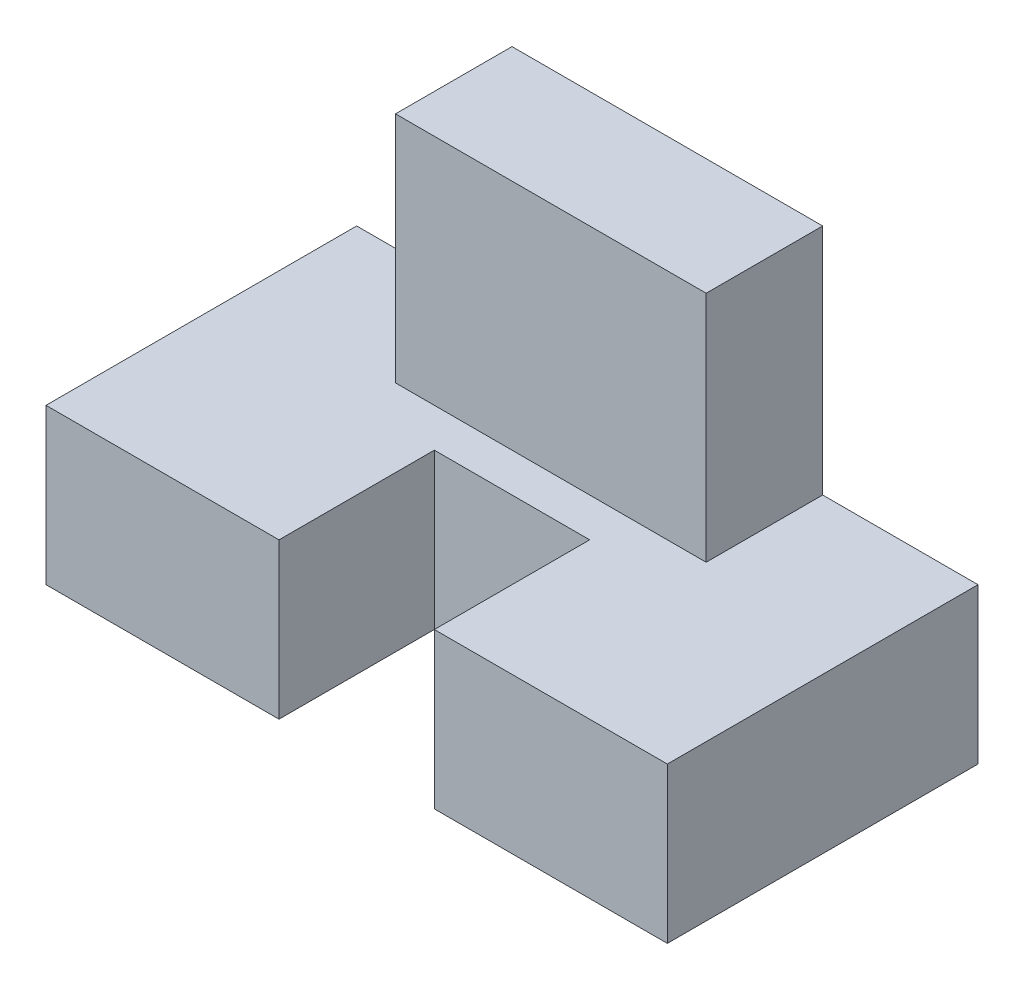
SolidWorks part; units mm, degrees
ref_plane "Front Plane" through (0, 0, 0) normal (0, 0, 1) x (1, 0, 0)
ref_plane "Top Plane" through (0, 0, 0) normal (0, 1, 0) x (1, 0, 0)
ref_plane "Right Plane" through (0, 0, 0) normal (1, 0, 0) x (0, 0, -1)
sketch "Sketch3" plane through (0, 0, 0) normal (0, 1, 0) x (1, 0, 0)
  line L8 (38.1, 0) -> (38.1, 25.4)
  line L9 (0, 0) -> (38.1, 0)
  line L10 (0, 0) -> (0, 50.8)
  line L11 (0, 50.8) -> (101.6, 50.8)
  line L12 (101.6, 0) -> (101.6, 50.8)
  line L13 (38.1, 25.4) -> (63.5, 25.4)
  line L14 (63.5, 25.4) -> (63.5, 0)
  line L15 (63.5, 0) -> (101.6, 0)
  dimension "D1" = 38.1
  dimension "D2" = 25.4
  dimension "D3" = 25.4
  dimension "D4" = 50.8
  dimension "D5" = 101.6
extrude "Boss-Extrude1" add sketch "Sketch3" along normal blind 25.4
sketch "Sketch6" plane through (0, 25.4, 0) normal (0, 1, 0) x (1, 0, 0)
  line L0 (25.4, 50.8) -> (25.4, 31.75)
  line L1 (101.6, 50.8) -> (0, 50.8) construction
  line L2 (25.4, 31.75) -> (76.2, 31.75)
  line L3 (76.2, 31.75) -> (76.2, 50.8)
  line L4 (101.6, 0) -> (101.6, 50.8) construction
  line L13 (0, 50.8) -> (0, 0)
  line L14 (0, 0) -> (38.1, 0)
  line L15 (38.1, 0) -> (38.1, 25.4)
  line L16 (38.1, 25.4) -> (63.5, 25.4)
  line L17 (63.5, 25.4) -> (63.5, 0)
  line L18 (63.5, 0) -> (101.6, 0)
  line L19 (101.6, 0) -> (101.6, 50.8)
  line L20 (101.6, 50.8) -> (0, 50.8)
  line L28 (76.2, 50.8) -> (25.4, 50.8)
  dimension "D1" = 19.05
  dimension "D2" = 76.2
  dimension "D3" = 25.4
  dimension "D4" = 0
extrude "Boss-Extrude2" add sketch "Sketch6" along normal blind 38.1
